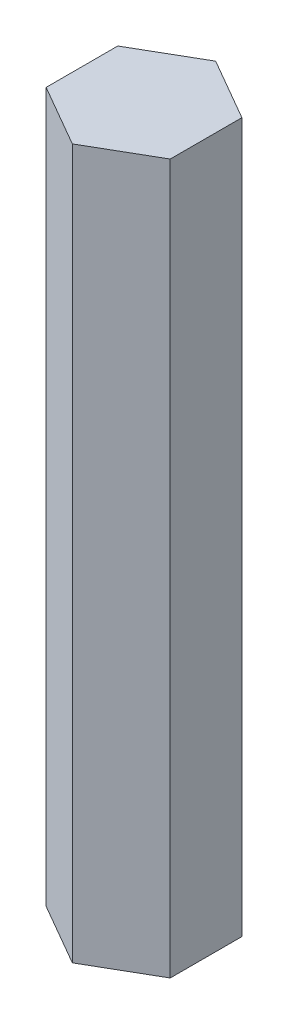
SolidWorks part; units mm, degrees
ref_plane "Спереди" through (0, 0, 0) normal (0, 0, 1) x (1, 0, 0)
ref_plane "Сверху" through (0, 0, 0) normal (0, 1, 0) x (1, 0, 0)
ref_plane "Справа" through (0, 0, 0) normal (1, 0, 0) x (0, 0, -1)
other "Configuration Table"
sketch "Эскиз1" plane through (0, 0, 0) normal (0, 1, 0) x (1, 0, 0)
  line L1 (0, 4.0415) -> (-3.5, 2.0207)
  line L2 (-3.5, 2.0207) -> (-3.5, -2.0207)
  line L3 (-3.5, -2.0207) -> (0, -4.0415)
  line L4 (0, -4.0415) -> (3.5, -2.0207)
  line L5 (3.5, -2.0207) -> (3.5, 2.0207)
  line L6 (3.5, 2.0207) -> (0, 4.0415)
  circle A0 centre (0, 0) radius 3.5 construction
extrude "Бобышка-Вытянуть1" add sketch "Эскиз1" along normal blind 40
